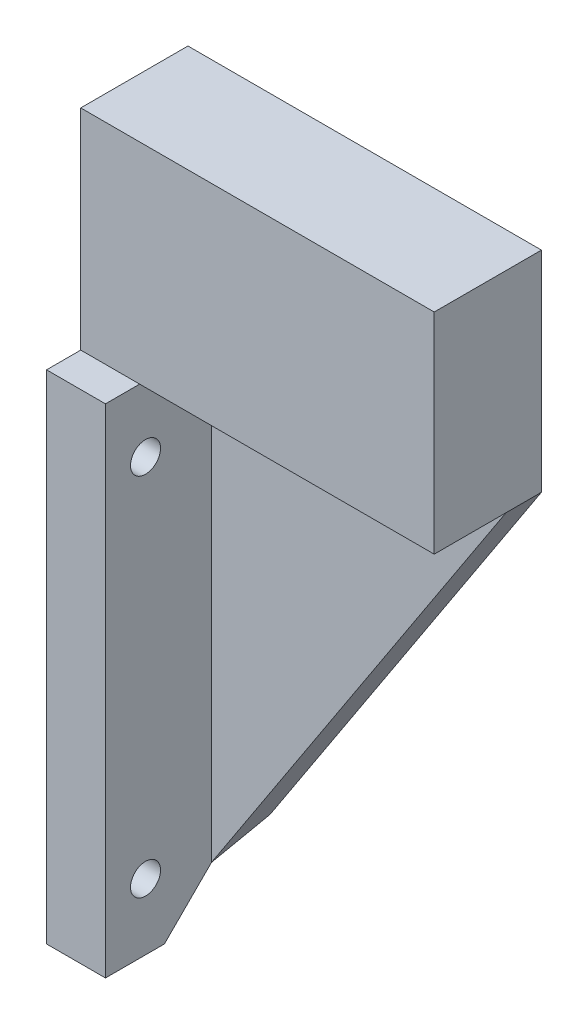
SolidWorks part; units mm, degrees
ref_plane "Front Plane" through (0, 0, 0) normal (0, 0, 1) x (1, 0, 0)
ref_plane "Top Plane" through (0, 0, 0) normal (0, 1, 0) x (1, 0, 0)
ref_plane "Right Plane" through (0, 0, 0) normal (1, 0, 0) x (0, 0, -1)
sketch "Sketch1" plane through (0, 0, 0) normal (1, 0, 0) x (0, 0, -1)
  line L0 (-0.3826, 8.0214) -> (-6.4826, 8.0214)
  line L1 (-6.4826, 8.0214) -> (-9.3826, 8.0214)
  line L2 (-9.3826, 8.0214) -> (-9.3826, -34.1786)
  line L3 (-9.3826, -34.1786) -> (-4.3816, -34.1786)
  line L4 (-4.3816, -34.1786) -> (-0.3826, -30.1796)
  line L5 (-0.3826, -30.1796) -> (-0.3826, 8.0214)
  line L6 (-6.4826, 25.8214) -> (-6.4826, 8.0214)
  line L7 (-6.4826, 8.0214) -> (-0.3826, 8.0214)
  line L8 (-0.3826, 8.0214) -> (2.6174, 8.0214)
  line L9 (2.6174, 8.0214) -> (2.6174, 25.8214)
  line L10 (2.6174, 25.8214) -> (-6.4826, 25.8214)
  circle A0 centre (-5.9826, -28.5786) radius 1.275
  circle A1 centre (-5.9826, 2.4214) radius 1.275
extrude "Boss-Extrude1" add sketch "Sketch1" along normal blind 5 contours L4 L5 L0 L1 L2 L3 A1 A0 | L9 L10 L6 L0 L8
sketch "Sketch2" plane through (5, 0, 0) normal (1, 0, 0) x (0, 0, -1)
  line L1 (-6.4826, 25.8214) -> (2.6174, 25.8214)
  line L2 (-6.4826, 25.8214) -> (-6.4826, 8.0214)
  line L3 (-6.4826, 8.0214) -> (2.6174, 8.0214)
  line L4 (2.6174, 25.8214) -> (2.6174, 8.0214)
extrude "Boss-Extrude2" add sketch "Sketch2" along normal blind 25
sketch "Sketch3" plane through (0, 0, 0.3826) normal (0, 0, -1) x (-1, 0, 0)
  line L1 (-30, 8.0214) -> (0, 8.0214)
  line L2 (0, 8.0214) -> (0, -30.1796)
  line L3 (0, -30.1796) -> (-5, -30.1796)
  line L4 (-5, -30.1796) -> (-30, 8.0214)
extrude "Boss-Extrude3" add sketch "Sketch3" along normal blind 3
sketch "Sketch4" plane through (5, 0, 0) normal (1, 0, 0) x (0, 0, -1)
  line L0 (-0.3826, -30.1796) -> (2.6174, -27.1796)
  line L1 (2.6174, 8.0214) -> (2.6174, -30.1796) construction
  line L2 (2.6174, -27.1796) -> (2.6174, -30.1796)
  line L3 (2.6174, -30.1796) -> (-0.3826, -30.1796)
extrude "Cut-Extrude1" cut sketch "Sketch4" against normal mid plane 30
